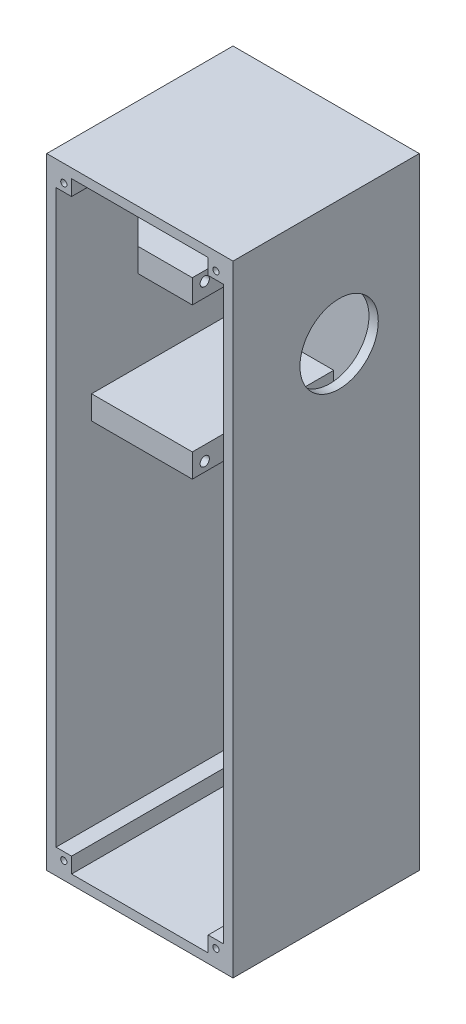
SolidWorks part; units mm, degrees
ref_plane "Płaszczyzna przednia" through (0, 0, 0) normal (0, 0, 1) x (1, 0, 0)
ref_plane "Płaszczyzna górna" through (0, 0, 0) normal (0, 1, 0) x (1, 0, 0)
ref_plane "Płaszczyzna prawa" through (0, 0, 0) normal (1, 0, 0) x (0, 0, -1)
sketch "Szkic1" plane through (0, 0, 0) normal (0, 1, 0) x (1, 0, 0)
  line L1 (0, 0) -> (60, 0)
  line L2 (0, 0) -> (0, 60)
  line L3 (0, 60) -> (60, 60)
  line L4 (60, 0) -> (60, 60)
  dimension "D1" = 60
  dimension "D2" = 60
extrude "Dodanie-wyciągnięcie1" add sketch "Szkic1" along normal blind 200
shell "Skorupa1" thickness 3
sketch "Szkic2" plane through (0, 0, -57) normal (0, 0, 1) x (1, 0, 0)
  line L1 (3, 197) -> (8, 197)
  line L2 (3, 197) -> (3, 192)
  line L3 (3, 192) -> (8, 192)
  line L4 (8, 197) -> (8, 192)
  circle A0 centre (5.5, 194.5) radius 1
  dimension "D3" = 2
  dimension "D1" = 5
  dimension "D2" = 5
extrude "Dodanie-wyciągnięcie2" add sketch "Szkic2" along normal blind 57
sketch "Szkic4" plane through (0, 0, 0) normal (0, 0, 1) x (1, 0, 0)
  line L1 (57, 197) -> (52, 197)
  line L2 (57, 197) -> (57, 192)
  line L3 (57, 192) -> (52, 192)
  line L4 (52, 197) -> (52, 192)
  circle A0 centre (54.5, 194.5) radius 1
  dimension "D2" = 2
  dimension "D1" = 5
extrude "Dodanie-wyciągnięcie3" add sketch "Szkic4" against normal blind 57
sketch "Szkic5" plane through (0, 0, -57) normal (0, 0, 1) x (1, 0, 0)
  line L1 (3, 3) -> (8, 3)
  line L2 (3, 3) -> (3, 8)
  line L3 (3, 8) -> (8, 8)
  line L4 (8, 3) -> (8, 8)
  circle A0 centre (5.5, 5.5) radius 1
  dimension "D2" = 2
  dimension "D1" = 5
extrude "Dodanie-wyciągnięcie4" add sketch "Szkic5" along normal blind 57
sketch "Szkic6" plane through (0, 0, -57) normal (0, 0, 1) x (1, 0, 0)
  line L1 (57, 3) -> (52, 3)
  line L2 (57, 3) -> (57, 8)
  line L3 (57, 8) -> (52, 8)
  line L4 (52, 3) -> (52, 8)
  circle A0 centre (54.5, 5.5) radius 1
  dimension "D2" = 2
  dimension "D1" = 5
extrude "Dodanie-wyciągnięcie6" add sketch "Szkic6" along normal blind 57
sketch "Szkic9" plane through (60, 0, 0) normal (1, 0, 0) x (0, 0, -1)
  line L0 (0, 200) -> (60, 200) construction
  line L1 (0, 200) -> (0, 0) construction
  circle A0 centre (34.18, 159.82) radius 12.625
  dimension "D1" = 25.25
  dimension "D2" = 40.18
  dimension "D3" = 34.18
extrude "Wytnij-wyciągnięcie1" cut sketch "Szkic9" against normal blind 3
sketch "Szkic10" plane through (3, 0, 0) normal (1, 0, 0) x (0, 0, -1)
  line L1 (11.45, 169.76) -> (57, 169.76)
  line L2 (11.45, 169.76) -> (11.45, 177.36)
  line L3 (11.45, 177.36) -> (57, 177.36)
  line L4 (57, 169.76) -> (57, 177.36)
  line L6 (0, 197) -> (57, 197) construction
  line L7 (11.45, 128.76) -> (57, 128.76)
  line L8 (11.45, 128.76) -> (11.45, 121.16)
  line L9 (11.45, 121.16) -> (57, 121.16)
  line L10 (57, 128.76) -> (57, 121.16)
  line L12 (0, 192) -> (57, 192) construction
  line L13 (0, 192) -> (0, 8) construction
  dimension "D1" = 45.55
  dimension "D2" = 7.6
  dimension "D3" = 27.24
  dimension "D4" = 63.24
  dimension "D5" = 45.55
  dimension "D6" = 7.6
  dimension "D7" = 11.45
  dimension "D8" = 11.45
extrude "Dodanie-wyciągnięcie7" add sketch "Szkic10" along normal blind 32.45
sketch "Szkic13" plane through (35.45, 0, 0) normal (1, 0, 0) x (0, 0, -1)
  line L0 (11.45, 177.36) -> (11.45, 169.76) construction
  line L5 (57, 177.36) -> (11.45, 177.36) construction
  circle A0 centre (25.1, 174.36) radius 1.5
  circle A1 centre (15.45, 174.36) radius 1.5
  dimension "D1" = 3
  dimension "D2" = 4
  dimension "D3" = 3
  dimension "D5" = 3
  dimension "D6" = 3
  dimension "D4" = 13.65
extrude "Wytnij-wyciągnięcie4" cut sketch "Szkic13" against normal blind 5
sketch "Szkic14" plane through (35.45, 0, 0) normal (1, 0, 0) x (0, 0, -1)
  line L0 (11.45, 128.76) -> (11.45, 121.16) construction
  line L6 (11.45, 121.16) -> (57, 121.16) construction
  circle A0 centre (25.6, 124.16) radius 1.5
  circle A1 centre (15.45, 124.16) radius 1.5
  dimension "D1" = 3
  dimension "D2" = 4
  dimension "D3" = 3
  dimension "D5" = 3
  dimension "D6" = 3
  dimension "D4" = 14.15
extrude "Wytnij-wyciągnięcie5" cut sketch "Szkic14" against normal blind 5
sketch "Szkic15" plane through (0, 177.36, 0) normal (0, 1, 0) x (1, 0, 0)
  line L0 (35.45, 11.45) -> (17.95, 11.45)
  line L1 (35.45, 11.45) -> (3, 11.45) construction
  line L2 (17.95, 11.45) -> (3, 11.45)
  line L3 (3, 11.45) -> (3, 26.45)
  line L4 (3, 57) -> (3, 11.45) construction
  line L5 (3, 26.45) -> (17.95, 11.45)
  dimension "D1" = 17.5
  dimension "D2" = 15
extrude "Wytnij-wyciągnięcie7" cut sketch "Szkic15" against normal blind 10 contours L2 L3 L5
